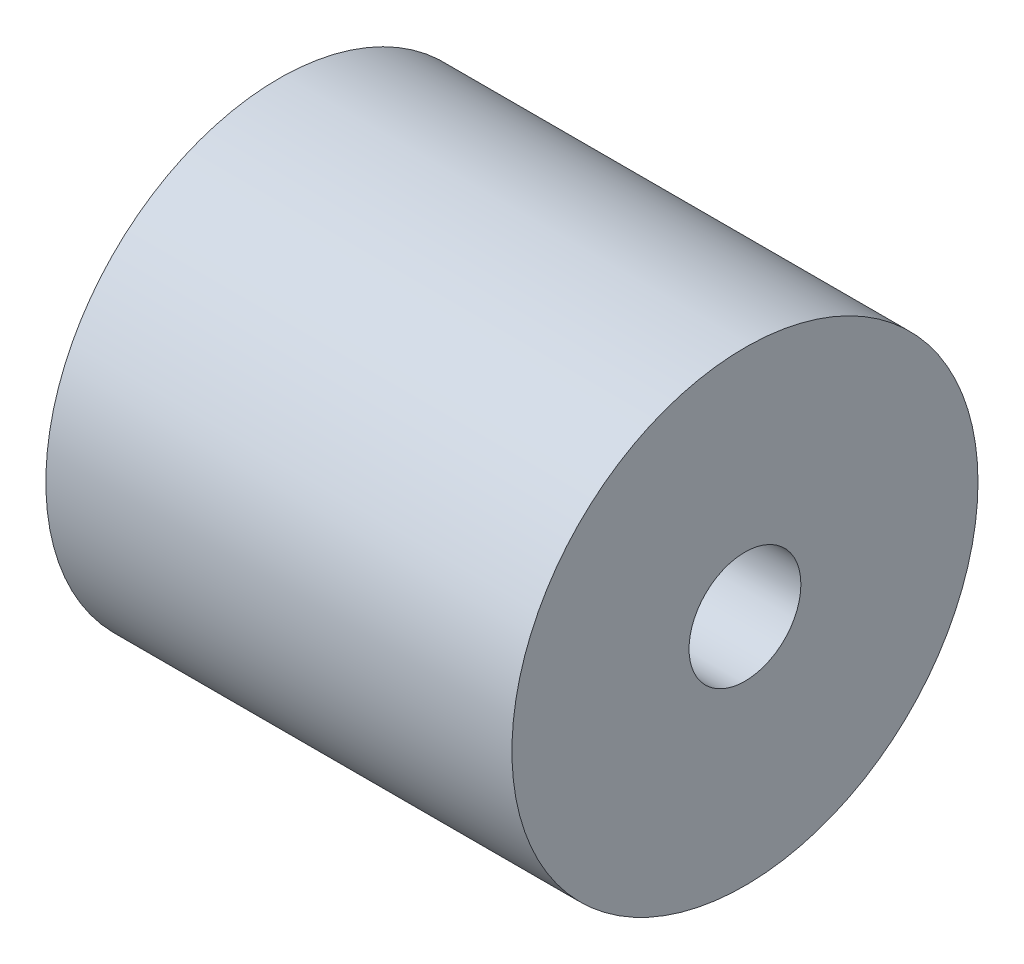
SolidWorks part; units mm, degrees
ref_plane "Front Plane" through (0, 0, 0) normal (0, 0, 1) x (1, 0, 0)
ref_plane "Top Plane" through (0, 0, 0) normal (0, 1, 0) x (1, 0, 0)
ref_plane "Right Plane" through (0, 0, 0) normal (1, 0, 0) x (0, 0, -1)
sketch "Sketch1" plane through (0, 0, 0) normal (0, 0, 1) x (1, 0, 0)
  line L0 (0, 0) -> (-25, 0) construction
  line L1 (-25, 2) -> (-25, 12.5)
  line L2 (-25, 12.5) -> (0, 12.5)
  line L3 (0, 12.5) -> (0, 3)
  line L4 (0, 3) -> (-12.5, 3)
  line L5 (-12.5, 3) -> (-12.5, 2)
  line L6 (-12.5, 2) -> (-25, 2)
  line L7 (-12.5, 12.5) -> (-12.5, 3) construction
  dimension "D1" = 25
  dimension "D2" = 4
  dimension "D3" = 6
  dimension "D4" = 25
revolve "Revolve1" add sketch "Sketch1" angle 360 about L0
